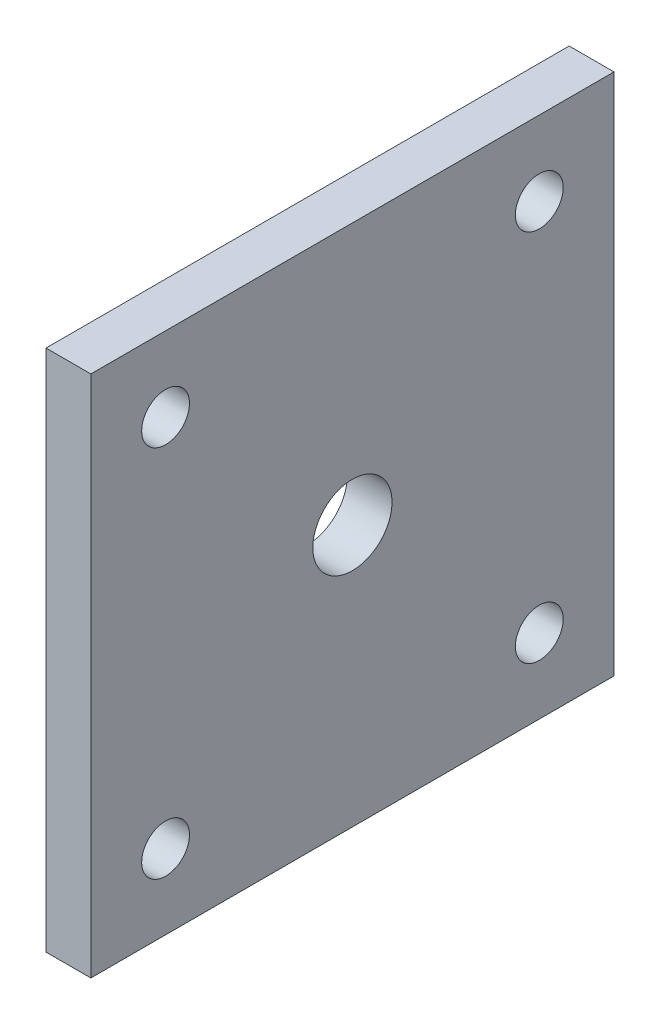
SolidWorks part; units mm, degrees
ref_plane "Front Plane" through (0, 0, 0) normal (0, 0, 1) x (1, 0, 0)
ref_plane "Top Plane" through (0, 0, 0) normal (0, 1, 0) x (1, 0, 0)
ref_plane "Right Plane" through (0, 0, 0) normal (1, 0, 0) x (0, 0, -1)
other "Configuration Table"
sketch "Sketch1" plane through (0, 0, 0) normal (1, 0, 0) x (0, 0, -1)
  line L0 (0, 12.5) -> (0, 17.5) construction
  line L1 (-17.5, 17.5) -> (17.5, 17.5)
  line L2 (-17.5, 17.5) -> (-17.5, -17.5)
  line L3 (-17.5, -17.5) -> (17.5, -17.5)
  line L4 (17.5, 17.5) -> (17.5, -17.5)
  line L5 (-17.5, 17.5) -> (17.5, -17.5) construction
  line L6 (-17.5, -17.5) -> (17.5, 17.5) construction
  line L7 (-12.5, 12.5) -> (12.5, 12.5) construction
  line L8 (-12.5, 12.5) -> (-12.5, -12.5) construction
  line L9 (-12.5, -12.5) -> (12.5, -12.5) construction
  line L10 (12.5, 12.5) -> (12.5, -12.5) construction
  line L11 (-12.5, 12.5) -> (12.5, -12.5) construction
  line L12 (-12.5, -12.5) -> (12.5, 12.5) construction
  point P0 (0, 0)
  point P6 (0, 0)
  dimension "D1" = 25
  dimension "D2" = 5
extrude "Boss-Extrude1" add sketch "Sketch1" along normal blind 3
sketch "Sketch2" plane through (0, 0, 0) normal (-1, 0, 0) x (0, 0, 1)
  circle A0 centre (-12.5, 12.5) radius 1.6
  circle A1 centre (-12.5, -12.5) radius 1.6
  circle A2 centre (12.5, -12.5) radius 1.6
  circle A3 centre (12.5, 12.5) radius 1.6
  dimension "D1" = 3.2
extrude "Cut-Extrude1" cut sketch "Sketch2" against normal through all
sketch "Sketch3" plane through (0, 0, 0) normal (-1, 0, 0) x (0, 0, 1)
  circle A0 centre (0, 0) radius 2.65
  dimension "D1" = 5.3
extrude "Cut-Extrude2" cut sketch "Sketch3" against normal through all
